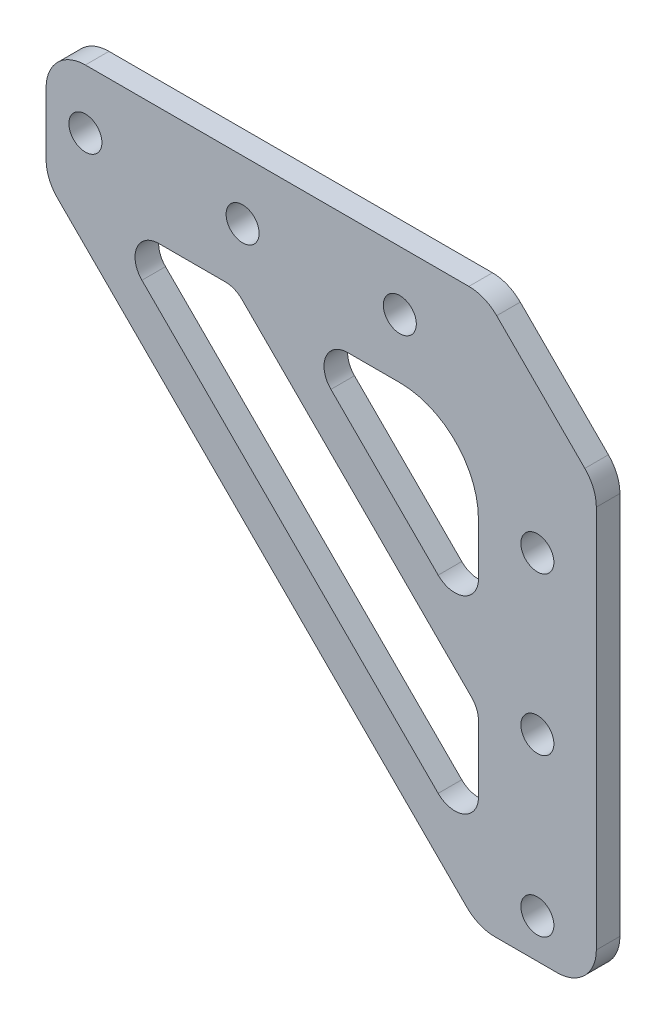
SolidWorks part; units mm, degrees
ref_plane "前视基准面" through (0, 0, 0) normal (0, 0, 1) x (1, 0, 0)
ref_plane "上视基准面" through (0, 0, 0) normal (0, 1, 0) x (1, 0, 0)
ref_plane "右视基准面" through (0, 0, 0) normal (1, 0, 0) x (0, 0, -1)
sketch "草图1" plane through (0, 0, 0) normal (0, 0, 1) x (1, 0, 0)
  line L0 (0, 0) -> (-70, 0)
  line L1 (-70, 0) -> (-70, -15)
  line L2 (-70, -15) -> (-15, -15)
  line L6 (-70, -7.5) -> (49930, -7.5) construction
  line L7 (0, 0) -> (-35355.3391, -35355.3391) construction
  line L8 (-15, -70) -> (-15, -15)
  line L9 (0, -70) -> (-15, -70)
  line L10 (0, 0) -> (0, -70)
  circle A1 centre (-25, -7.5) radius 2.1
  circle A2 centre (-7.5, -25) radius 2.1
  circle A4 centre (-45, -7.5) radius 2.1
  circle A5 centre (-65, -7.5) radius 2.1
  circle A6 centre (-7.5, -65) radius 2.1
  circle A7 centre (-7.5, -45) radius 2.1
  point P9 (-70, -7.5)
  dimension "D3" = 3
  dimension "D4" = 4.2
  dimension "D1" = 15
  dimension "D2" = 45
  dimension "D5" = 25
  dimension "D6" = 20
  dimension "D7" = 70
extrude "凸台-拉伸1" add sketch "草图1" along normal blind 3
sketch "草图2" plane through (0, 0, 3) normal (0, 0, 1) x (1, 0, 0)
  line L0 (-70, -15) -> (-15, -70)
  line L1 (-15, -70) -> (-15, -62.9289)
  line L2 (-15, -15) -> (-15, -70) construction
  line L3 (-15, -62.9289) -> (-62.9289, -15)
  line L4 (-70, -15) -> (-15, -15) construction
  line L5 (-62.9289, -15) -> (-70, -15)
  dimension "D1" = 5
extrude "凸台-拉伸2" add sketch "草图2" against normal blind 3
sketch "草图3" plane through (0, 0, 3) normal (0, 0, 1) x (1, 0, 0)
  line L0 (-14.1421, 0) -> (0, -14.1421)
  line L1 (0, 0) -> (-70, 0) construction
  line L2 (0, -70) -> (0, 0) construction
  line L3 (-15, -62.9289) -> (-62.9289, -15) construction
  dimension "D1" = 10
extrude "切除-拉伸1" cut sketch "草图3" against normal blind 3 and the other way through all
fillet "圆角1" radius 5 6 edges at (-15, -70, 1.5) (0, -70, 1.5) (-70, -15, 1.5) (-70, 0, 1.5) (0, -14.1421, 1.5) (-14.1421, 0, 1.5)
sketch "草图4" plane through (0, 0, 3) normal (0, 0, 1) x (1, 0, 0)
  line L0 (-45.9584, -15) -> (-15, -45.9584)
  line L1 (-62.9289, -15) -> (-15, -15) construction
  line L2 (-15, -15) -> (-15, -62.9289) construction
  line L3 (-15, -45.9584) -> (-15, -38.8873)
  line L4 (-15, -38.8873) -> (-38.8873, -15)
  line L5 (-38.8873, -15) -> (-45.9584, -15)
  line L6 (-68.5355, -16.4645) -> (-16.4645, -68.5355) construction
  line L7 (-15, -62.9289) -> (-62.9289, -15) construction
  dimension "D1" = 5
  dimension "D2" = 12
extrude "凸台-拉伸3" add sketch "草图4" against normal through all
fillet "圆角2" radius 3 6 edges at (-15, -62.9289, 1.5) (-62.9289, -15, 1.5) (-15, -45.9584, 1.5) (-45.9584, -15, 1.5) (-15, -38.8873, 1.5) (-38.8873, -15, 1.5)
fillet "圆角3" radius 10 1 edges at (-15, -15, 1.5)
